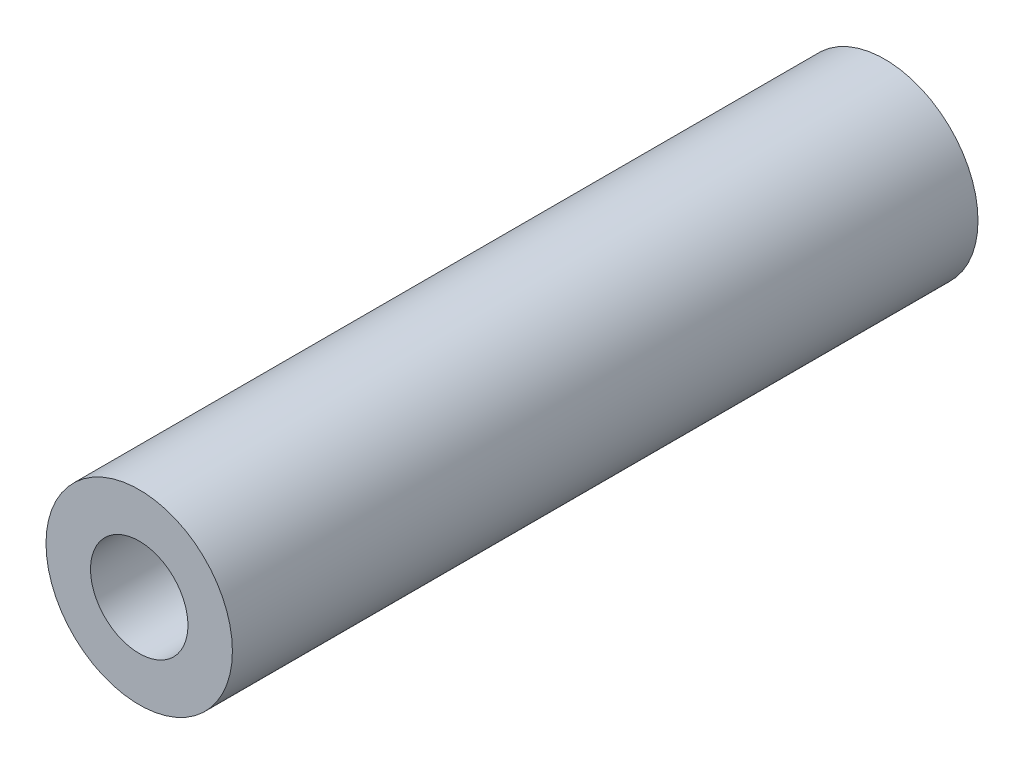
SolidWorks part; units mm, degrees
material "6061-T6 (SS)"
ref_plane "Front Plane" through (0, 0, 0) normal (0, 0, 1) x (1, 0, 0)
ref_plane "Top Plane" through (0, 0, 0) normal (0, 1, 0) x (1, 0, 0)
ref_plane "Right Plane" through (0, 0, 0) normal (1, 0, 0) x (0, 0, -1)
sketch "Sketch1" plane through (0, 0, 0) normal (0, 0, 1) x (1, 0, 0)
  circle A0 centre (0, 0) radius 4.7625
  circle A1 centre (0, 0) radius 2.4892
  dimension "D1" = 4.9784
  dimension "D2" = 9.525
extrude "Boss-Extrude1" add sketch "Sketch1" along normal blind 38.1
